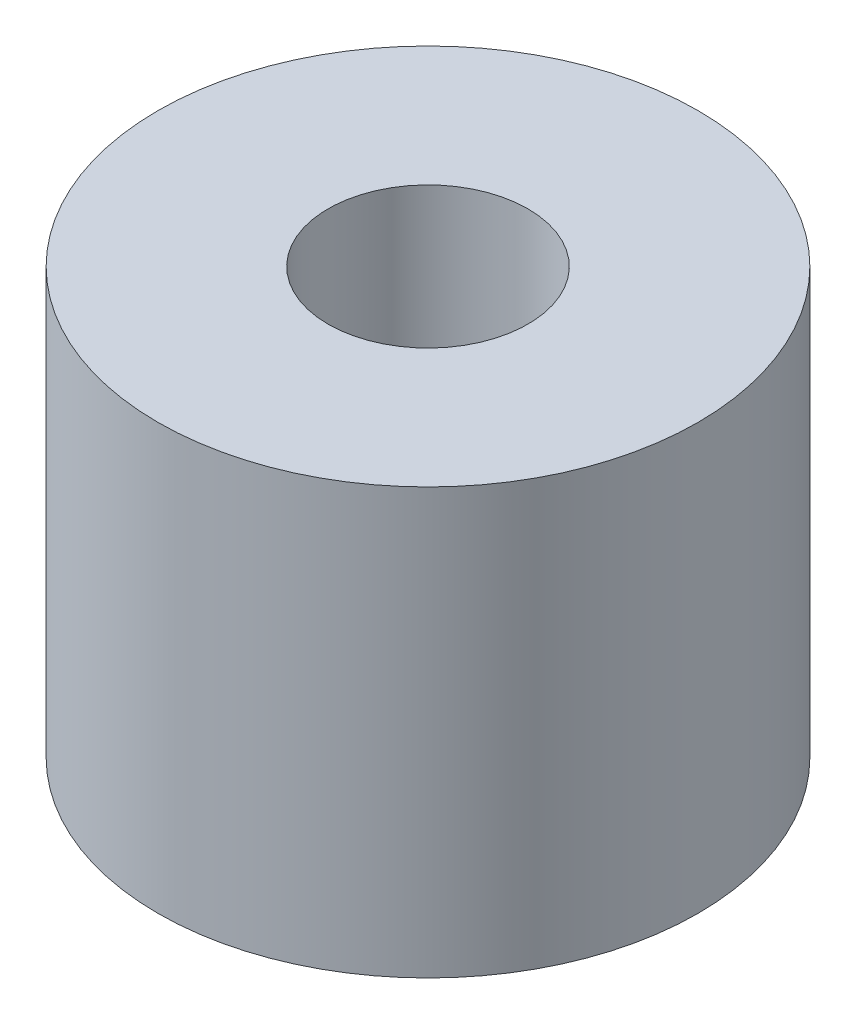
SolidWorks part; units mm, degrees
ref_plane "Front Plane" through (0, 0, 0) normal (0, 0, 1) x (1, 0, 0)
ref_plane "Top Plane" through (0, 0, 0) normal (0, 1, 0) x (1, 0, 0)
ref_plane "Right Plane" through (0, 0, 0) normal (1, 0, 0) x (0, 0, -1)
sketch "Sketch1" plane through (0, 0, 0) normal (0, 1, 0) x (1, 0, 0)
  circle A0 centre (0, 0) radius 1.175
  circle A1 centre (0, 0) radius 3.175
  dimension "D1" = 2.35
  dimension "D2" = 2
extrude "Boss-Extrude1" add sketch "Sketch1" along normal blind 5
